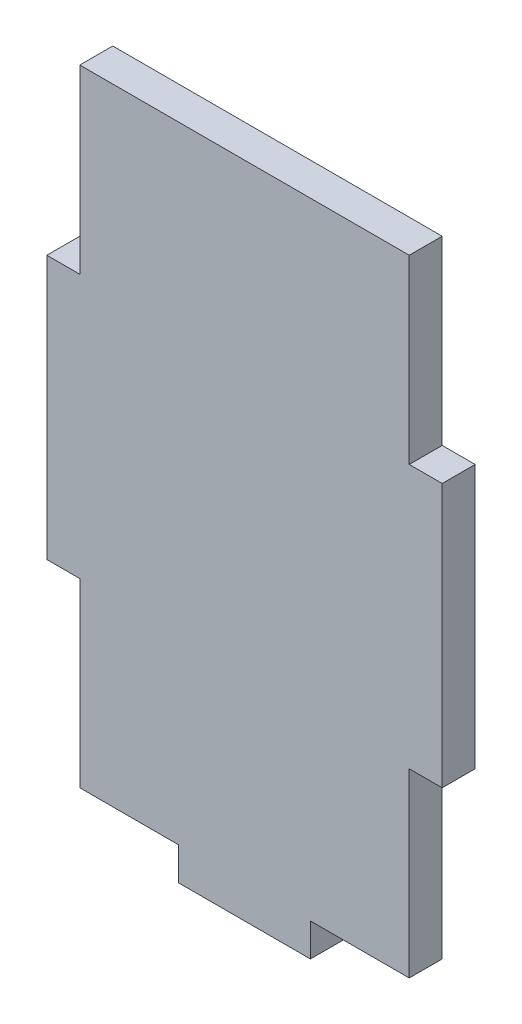
SolidWorks part; units mm, degrees
ref_plane "Plan de face" through (0, 0, 0) normal (0, 0, 1) x (1, 0, 0)
ref_plane "Plan de dessus" through (0, 0, 0) normal (0, 1, 0) x (1, 0, 0)
ref_plane "Plan de droite" through (0, 0, 0) normal (1, 0, 0) x (0, 0, -1)
sketch "Sketch1" plane through (0, 0, 0) normal (0, 0, 1) x (1, 0, 0)
  line L0 (-31.75, -25.4) -> (-31.75, -60.325)
  line L1 (-31.75, 60.325) -> (31.75, 60.325)
  line L2 (-31.75, 60.325) -> (-31.75, 25.4)
  line L3 (-31.75, -60.325) -> (-12.7, -60.325)
  line L5 (-31.75, 60.325) -> (0, 0) construction
  line L6 (-31.75, -60.325) -> (0, 0) construction
  line L16 (-12.7, -60.325) -> (-12.7, -66.675)
  line L17 (-12.7, -66.675) -> (12.7, -66.675)
  line L19 (0, 60.325) -> (0, -66.675) construction
  line L20 (38.1, 0) -> (-38.1, 0) construction
  line L21 (-31.75, 25.4) -> (-38.1, 25.4)
  line L23 (-31.75, -25.4) -> (-38.1, -25.4)
  line L24 (-38.1, 25.4) -> (-38.1, -25.4)
  line L26 (31.75, -60.325) -> (0, 0) construction
  line L31 (31.75, 60.325) -> (0, 0) construction
  line L32 (38.1, 25.4) -> (38.1, -25.4)
  line L34 (31.75, -25.4) -> (38.1, -25.4)
  line L35 (31.75, 25.4) -> (38.1, 25.4)
  line L36 (12.7, -60.325) -> (12.7, -66.675)
  line L37 (31.75, -60.325) -> (12.7, -60.325)
  line L38 (31.75, 60.325) -> (31.75, 25.4)
  line L39 (31.75, -25.4) -> (31.75, -60.325)
  point P0 (0, 0)
  point P1 (0, 0)
  point P9 (14.2792, -66.675)
  point P12 (-38.1, 0)
  point P13 (-25.4, -82.137)
  dimension "D5" = 6.35
  dimension "D7" = 50.8
  dimension "D3" = 6.35
  dimension "D4" = 25.4
  dimension "D6" = 76.2
  dimension "D1" = 127
extrude "Boss-Extrude1" add sketch "Sketch1" along normal mid plane 6.35
equation "\"vee_block_width\" = 3in"
equation "\"material_thickness\" = 0.25in"
equation "\"D5@Sketch1\"=\"material_thickness\""
equation "\"D3@Sketch1\"=\"material_thickness\""
equation "\"D6@Sketch1\"=\"vee_block_width\""
equation "\"D1@Sketch1\"=5"
equation "\"D4@Sketch1\"=1"
equation "\"D1@Sketch2\"=0.25"
